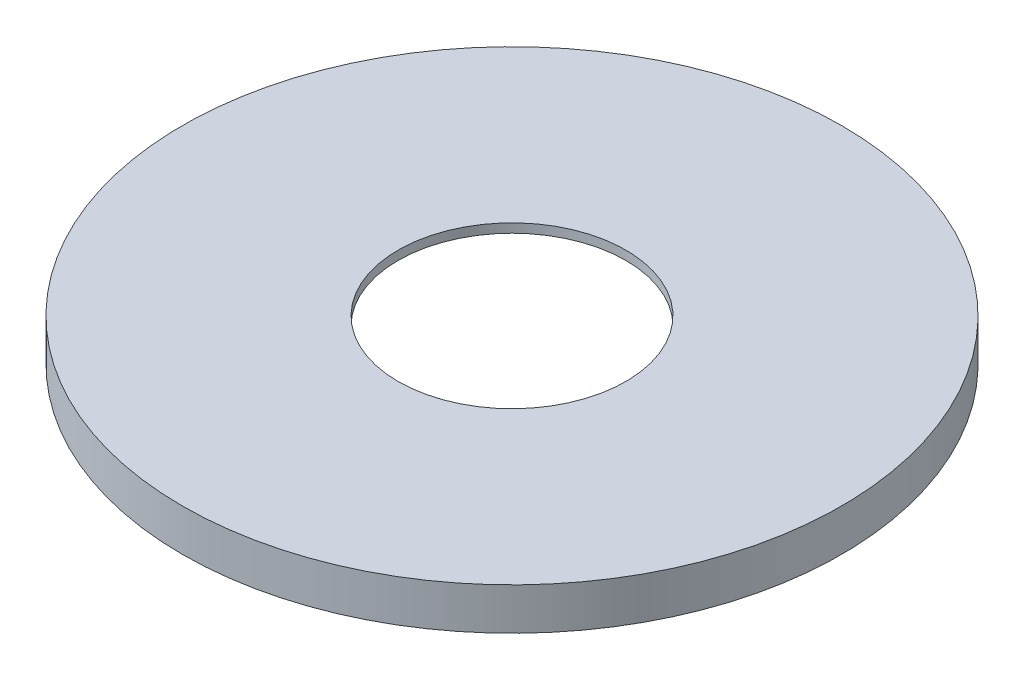
SolidWorks part; units mm, degrees
ref_plane "Alzado" through (0, 0, 0) normal (0, 0, 1) x (1, 0, 0)
ref_plane "Planta" through (0, 0, 0) normal (0, 1, 0) x (1, 0, 0)
ref_plane "Vista lateral" through (0, 0, 0) normal (1, 0, 0) x (0, 0, -1)
sketch "Croquis1" plane through (0, 0, 0) normal (0, 1, 0) x (1, 0, 0)
  circle A0 centre (0, 0) radius 55
  dimension "D1" = 110
extrude "Saliente-Extruir1" add sketch "Croquis1" along normal blind 7
sketch "Croquis2" plane through (0, 0, 0) normal (0, -1, 0) x (1, 0, 0)
  circle A0 centre (0, 0) radius 51
  dimension "D1" = 102
extrude "Cortar-Extruir1" cut sketch "Croquis2" against normal blind 5.5
sketch "Croquis3" plane through (0, 7, 0) normal (0, 1, 0) x (1, 0, 0)
  circle A0 centre (0, 0) radius 19
  dimension "D1" = 38
extrude "Cortar-Extruir2" cut sketch "Croquis3" against normal up to next
